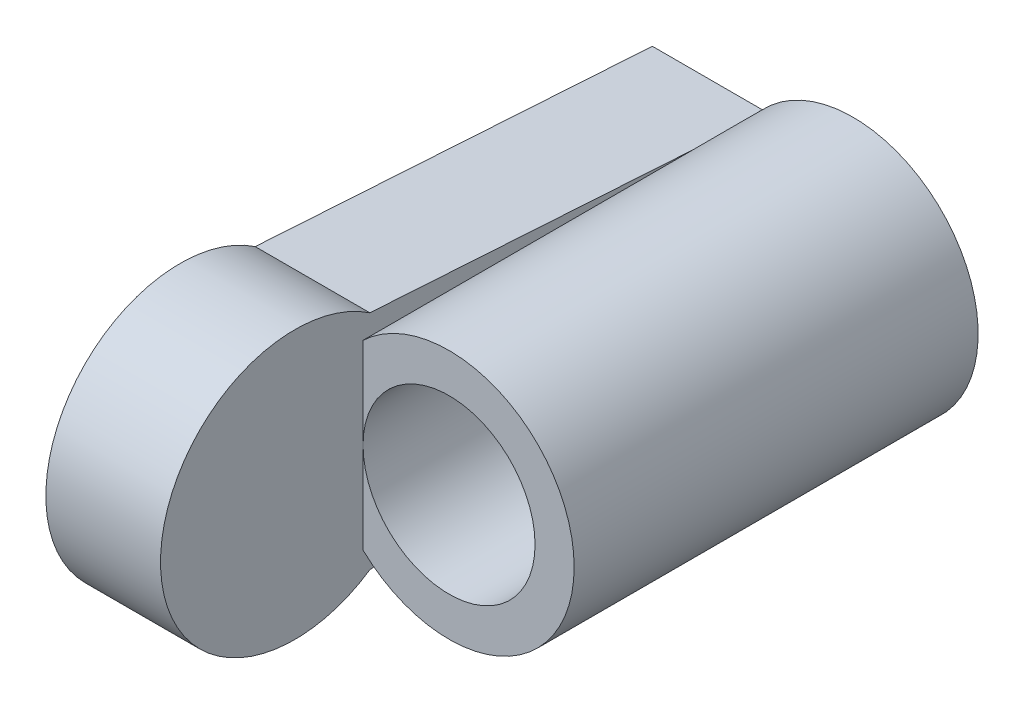
SolidWorks part; units mm, degrees
ref_plane "Front Plane" through (0, 0, 0) normal (0, 0, 1) x (1, 0, 0)
ref_plane "Top Plane" through (0, 0, 0) normal (0, 1, 0) x (1, 0, 0)
ref_plane "Right Plane" through (0, 0, 0) normal (1, 0, 0) x (0, 0, -1)
sketch "Sketch1" plane through (0, 0, 0) normal (1, 0, 0) x (0, 0, -1)
  line L0 (0, 16.3489) -> (0, -13.6511) construction
  line L1 (17.8058, 0) -> (-16.295, 0) construction
  line L2 (2.3415, 2.8) -> (12.6267, 2.15)
  line L3 (12.6267, 2.15) -> (16.6188, 1.8977)
  line L4 (16.6188, 1.8977) -> (16.6188, -1.8977)
  line L5 (12.6267, -2.15) -> (16.6188, -1.8977)
  line L6 (2.3415, -2.8) -> (12.6267, -2.15)
  line L7 (2.8808, 4.2689) -> (12.7213, 3.647)
  line L8 (12.7213, 3.647) -> (18.1188, 3.3059)
  line L9 (18.1188, 3.3059) -> (18.1188, -3.3059)
  line L10 (12.7213, -3.647) -> (18.1188, -3.3059)
  line L11 (2.8808, -4.2689) -> (12.7213, -3.647)
  arc A0 (2.3415, 2.8) -> (2.3415, -2.8) centre (0, 0) ccw
  arc A1 (2.8808, 4.2689) -> (2.8808, -4.2689) centre (0, 0) ccw
  point P12 (16.6188, 0)
  dimension "D2" = 7.3
  dimension "D1" = 30
  dimension "D3" = 10.3058
  dimension "D4" = 2.15
  dimension "D5" = 2.8
  dimension "D6" = 4
  dimension "D7" = 1.5
extrude "Boss-Extrude1" add sketch "Sketch1" along normal blind 3
sketch "Sketch2" plane through (3, 0, 0) normal (1, 0, 0) x (0, 0, -1)
  line L3 (2.8808, -4.2689) -> (18.1188, -3.3059)
  line L4 (18.1188, -3.3059) -> (18.1188, 3.3059)
  line L5 (18.1188, 3.3059) -> (2.8808, 4.2689)
  line L6 (2.8808, -4.2689) -> (18.1188, -3.3059)
  line L7 (18.1188, -3.3059) -> (18.1188, 3.3059)
  line L8 (18.1188, 3.3059) -> (2.8808, 4.2689)
  arc A1 (2.8808, 4.2689) -> (2.8808, -4.2689) centre (0, 0) ccw
  arc A2 (2.8808, 4.2689) -> (2.8808, -4.2689) centre (0, 0) ccw
  dimension "D1" = 0
extrude "Boss-Extrude2" add sketch "Sketch2" along normal blind 1.4
sketch "Sketch3" plane through (0, 0, -18.1188) normal (0, 0, -1) x (-1, 0, 0)
  line L0 (-4.4, -3.3059) -> (-4.4, 3.3059) construction
  circle A0 centre (-7.7, 0) radius 3.3
  circle A1 centre (-7.7, 0) radius 4.8
  dimension "D1" = 6.6
  dimension "D2" = 1.5
extrude "Boss-Extrude3" add sketch "Sketch3" against normal blind 15.5
sketch "Sketch4" plane through (0, 0, -18.1188) normal (0, 0, -1) x (-1, 0, 0)
  circle A0 centre (-7.7, 0) radius 1.65
  circle A1 centre (-7.7, 0) radius 3.3 construction
  circle A3 centre (-7.7, 0) radius 3.3
  dimension "D1" = 3.3
extrude "Boss-Extrude4" add sketch "Sketch4" against normal blind 1.5
sketch "Sketch5" plane through (0, 0, 0) normal (-1, 0, 0) x (0, 0, 1)
  line L0 (-16.6188, 1.8977) -> (-2.3415, 2.8) construction
  line L1 (-16.6188, 1.8977) -> (-2.3415, 2.8)
  line L2 (-2.3415, -2.8) -> (-16.6188, -1.8977) construction
  line L3 (-2.3415, -2.8) -> (-16.6188, -1.8977)
  line L4 (-16.6188, -1.8977) -> (-16.6188, 1.8977) construction
  line L5 (-16.6188, -1.8977) -> (-16.6188, 1.8977)
  arc A0 (-2.3415, -2.8) -> (-2.3415, 2.8) centre (0, 0) ccw construction
  arc A1 (-2.3415, -2.8) -> (-2.3415, 2.8) centre (0, 0) ccw
extrude "Cut-Extrude1" cut sketch "Sketch5" against normal up to surface (3 mm away) up to face at (3, 0, -8.8005)
